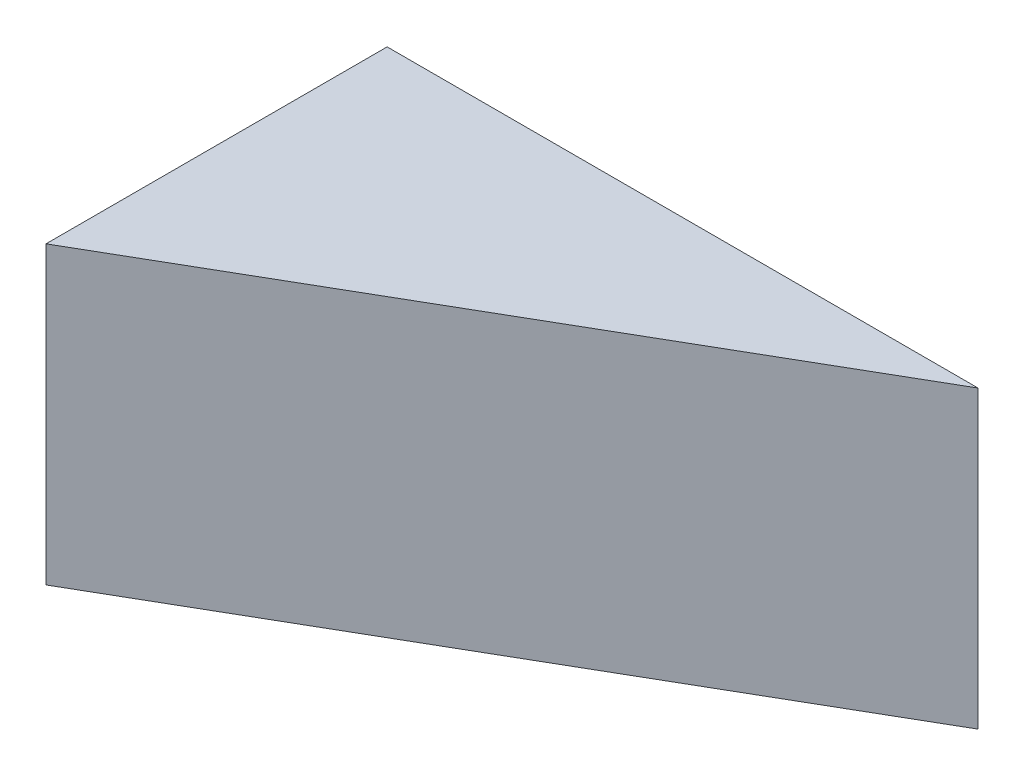
SolidWorks part; units mm, degrees
ref_plane "Přední rovina" through (0, 0, 0) normal (0, 0, 1) x (1, 0, 0)
ref_plane "Horní rovina" through (0, 0, 0) normal (0, 1, 0) x (1, 0, 0)
ref_plane "Pravá rovina" through (0, 0, 0) normal (1, 0, 0) x (0, 0, -1)
sketch "Sketch1" plane through (0, 0, 0) normal (0, 1, 0) x (1, 0, 0)
  line L0 (0, 0) -> (40, 0)
  line L1 (40, 0) -> (0, -23.094)
  line L2 (0, -23.094) -> (0, 0)
  point P4 (0, 0)
  point P5 (0, 0)
  dimension "D1" = 30
  dimension "D2" = 40
extrude "Boss-Extrude1" add sketch "Sketch1" along normal blind 20
